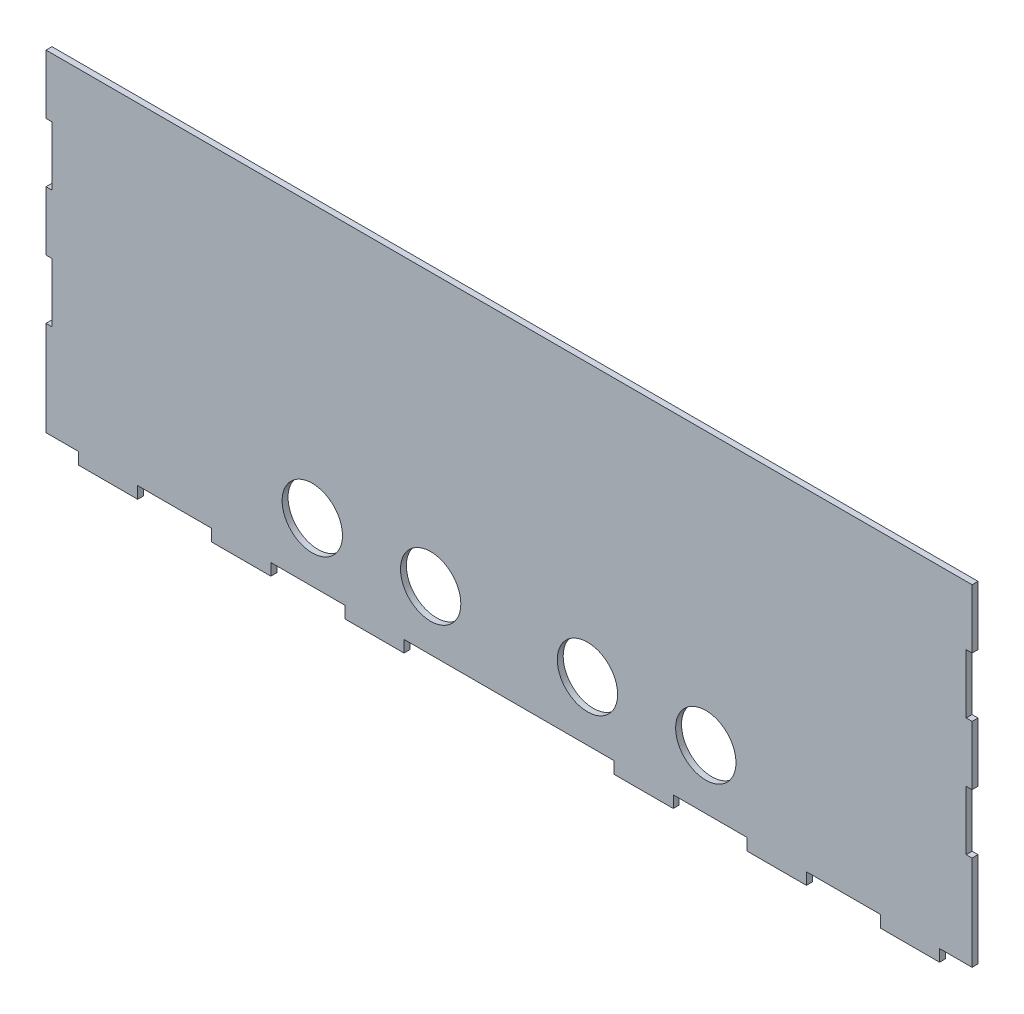
SolidWorks part; units mm, degrees
ref_plane "Front Plane" through (0, 0, 0) normal (0, 0, 1) x (1, 0, 0)
ref_plane "Top Plane" through (0, 0, 0) normal (0, 1, 0) x (1, 0, 0)
ref_plane "Right Plane" through (0, 0, 0) normal (1, 0, 0) x (0, 0, -1)
sketch "Sketch1" plane through (0, 0, 0) normal (0, 0, 1) x (1, 0, 0)
  line L0 (0, -55) -> (0, 55) construction
  line L1 (-156.5, -56) -> (-145.5, -56)
  line L2 (-156.5, -56) -> (-156.5, -24)
  line L3 (-156.5, 56) -> (-145.5, 56)
  line L4 (156.5, -56) -> (156.5, -24)
  line L5 (-156.5, -56) -> (156.5, 56) construction
  line L6 (-156.5, 56) -> (156.5, -56) construction
  line L7 (-100.5, -56) -> (-100.5, -60)
  line L9 (-145.5, -56) -> (-145.5, -60)
  line L10 (-145.5, -60) -> (-125.5, -60)
  line L11 (-125.5, -56) -> (-125.5, -60)
  line L13 (-80.5, -56) -> (-80.5, -60)
  line L14 (-100.5, -60) -> (-80.5, -60)
  line L15 (-55.5, -56) -> (-55.5, -60)
  line L17 (-35.5, -56) -> (-35.5, -60)
  line L18 (-55.5, -60) -> (-35.5, -60)
  line L20 (35.5, -56) -> (35.5, -60)
  line L21 (55.5, -60) -> (35.5, -60)
  line L22 (55.5, -56) -> (55.5, -60)
  line L24 (80.5, -56) -> (80.5, -60)
  line L25 (100.5, -60) -> (80.5, -60)
  line L26 (100.5, -56) -> (100.5, -60)
  line L27 (145.5, -60) -> (125.5, -60)
  line L28 (125.5, -56) -> (125.5, -60)
  line L30 (145.5, -56) -> (145.5, -60)
  line L31 (55.5, -56) -> (80.5, -56)
  line L32 (100.5, -56) -> (125.5, -56)
  line L33 (145.5, -56) -> (156.5, -56)
  line L34 (-125.5, -56) -> (-100.5, -56)
  line L35 (-80.5, -56) -> (-55.5, -56)
  line L36 (-35.5, -56) -> (35.5, -56)
  line L38 (-156.5, 36) -> (-154.5, 36)
  line L40 (-156.5, 16) -> (-154.5, 16)
  line L41 (-154.5, 36) -> (-154.5, 16)
  line L42 (-156.5, -4) -> (-154.5, -4)
  line L43 (-154.5, -4) -> (-154.5, -24)
  line L44 (-156.5, -24) -> (-154.5, -24)
  line L45 (156.5, -4) -> (154.5, -4)
  line L46 (154.5, -4) -> (154.5, -24)
  line L47 (156.5, -24) -> (154.5, -24)
  line L49 (156.5, 16) -> (154.5, 16)
  line L50 (154.5, 36) -> (154.5, 16)
  line L51 (156.5, 36) -> (154.5, 36)
  line L53 (-156.5, 36) -> (-156.5, 56)
  line L54 (-156.5, -4) -> (-156.5, 16)
  line L55 (156.5, 36) -> (156.5, 56)
  line L56 (156.5, -4) -> (156.5, 16)
  line L57 (-100.5, 56) -> (-100.5, 58)
  line L88 (-145.5, 56) -> (-145.5, 58)
  line L89 (-145.5, 58) -> (-125.5, 58)
  line L90 (-125.5, 56) -> (-125.5, 58)
  line L92 (-80.5, 56) -> (-80.5, 58)
  line L93 (-100.5, 58) -> (-80.5, 58)
  line L94 (-55.5, 56) -> (-55.5, 58)
  line L96 (-35.5, 56) -> (-35.5, 58)
  line L97 (-55.5, 58) -> (-35.5, 58)
  line L99 (35.5, 56) -> (35.5, 58)
  line L100 (55.5, 58) -> (35.5, 58)
  line L101 (55.5, 56) -> (55.5, 58)
  line L103 (80.5, 56) -> (80.5, 58)
  line L104 (100.5, 58) -> (80.5, 58)
  line L105 (100.5, 56) -> (100.5, 58)
  line L106 (145.5, 58) -> (125.5, 58)
  line L107 (125.5, 56) -> (125.5, 58)
  line L109 (145.5, 56) -> (145.5, 58)
  line L110 (-125.5, 56) -> (-100.5, 56)
  line L111 (-80.5, 56) -> (-55.5, 56)
  line L112 (-35.5, 56) -> (35.5, 56)
  line L113 (145.5, 56) -> (156.5, 56)
  line L114 (55.5, 56) -> (80.5, 56)
  line L115 (100.5, 56) -> (125.5, 56)
  circle A0 centre (-66.5, -36) radius 10.2
  circle A1 centre (-26.5, -36) radius 10.2
  circle A2 centre (26.5, -36) radius 10.2
  circle A3 centre (66.5, -36) radius 10.2
  point P0 (0, 0)
  dimension "D3" = 20.4
  dimension "D4" = 20.4
  dimension "D1" = 313
  dimension "D2" = 112
  dimension "D5" = 20
  dimension "D6" = 20
  dimension "D7" = 90
  dimension "D8" = 40
  dimension "D9" = 4
  dimension "D10" = 11
  dimension "D11" = 20
  dimension "D13" = 25
  dimension "D14" = 20
  dimension "D15" = 2
  dimension "D16" = 20
  dimension "D18" = 20
  dimension "D24" = 2
  dimension "D25" = 11
  dimension "D26" = 20
  dimension "D27" = 3
  dimension "D28" = 25
  dimension "D12" = 3
  dimension "D17" = 2
extrude "Boss-Extrude1" add sketch "Sketch1" along normal blind 2
sketch "Sketch2" plane through (0, 0, 2) normal (0, 0, 1) x (1, 0, 0)
  line L0 (145.5, -56) -> (156.5, -56) construction
  line L1 (134.5, -16) -> (114.5, -16)
  line L2 (134.5, -16) -> (134.5, -14)
  line L3 (134.5, -14) -> (114.5, -14)
  line L4 (114.5, -16) -> (114.5, -14)
  line L5 (134.5, -16) -> (114.5, -14) construction
  line L6 (134.5, -14) -> (114.5, -16) construction
  line L7 (154.5, -24) -> (154.5, -4) construction
  line L8 (104.5, -16) -> (104.5, -14)
  line L9 (104.5, -16) -> (84.5, -16)
  line L10 (84.5, -16) -> (84.5, -14)
  line L11 (104.5, -14) -> (84.5, -14)
  line L12 (74.5, -16) -> (74.5, -14)
  line L13 (74.5, -16) -> (54.5, -16)
  line L14 (54.5, -16) -> (54.5, -14)
  line L15 (74.5, -14) -> (54.5, -14)
  line L16 (-35.5, -56) -> (35.5, -56) construction
  line L17 (39.5, -16) -> (19.5, -16)
  line L18 (39.5, -16) -> (39.5, -14)
  line L19 (39.5, -14) -> (19.5, -14)
  line L20 (19.5, -16) -> (19.5, -14)
  line L21 (39.5, -16) -> (19.5, -14) construction
  line L22 (39.5, -14) -> (19.5, -16) construction
  line L23 (9.5, -16) -> (9.5, -14)
  line L24 (9.5, -16) -> (-10.5, -16)
  line L25 (-10.5, -16) -> (-10.5, -14)
  line L26 (9.5, -14) -> (-10.5, -14)
  line L27 (-20.5, -16) -> (-20.5, -14)
  line L28 (-20.5, -16) -> (-40.5, -16)
  line L29 (-40.5, -16) -> (-40.5, -14)
  line L30 (-20.5, -14) -> (-40.5, -14)
  line L31 (-50.5, -16) -> (-50.5, -14)
  line L32 (-50.5, -16) -> (-70.5, -16)
  line L33 (-70.5, -16) -> (-70.5, -14)
  line L34 (-50.5, -14) -> (-70.5, -14)
  point P0 (124.5, -15)
  point P10 (29.5, -15)
  dimension "D1" = 20
  dimension "D2" = 2
  dimension "D3" = 40
  dimension "D4" = 20
  dimension "D6" = 10
  dimension "D7" = 2
  dimension "D8" = 20
  dimension "D9" = 15
  dimension "D10" = 40
  dimension "D12" = 10
  dimension "D5" = 3
  dimension "D11" = 4
extrude "Cut-Extrude1" [suppressed] cut sketch "Sketch2" against normal blind 10
sketch "Sketch3" plane through (0, 0, 0) normal (0, 0, -1) x (-1, 0, 0)
  line L0 (-80.5, 56) -> (-55.5, 56) construction
  line L2 (-156.5, 36) -> (-156.5, 56) construction
  line L3 (-35.5, 56) -> (35.5, 56) construction
  line L4 (-46.5, 25.5) -> (-44.5, 25.5)
  line L5 (-46.5, 25.5) -> (-46.5, 40.5)
  line L6 (-46.5, 40.5) -> (-44.5, 40.5)
  line L7 (-44.5, 25.5) -> (-44.5, 40.5)
  line L8 (-46.5, 25.5) -> (-44.5, 40.5) construction
  line L9 (-46.5, 40.5) -> (-44.5, 25.5) construction
  line L10 (-68.5, 25.5) -> (-66.5, 25.5)
  line L11 (-68.5, 25.5) -> (-68.5, 40.5)
  line L12 (-68.5, 40.5) -> (-66.5, 40.5)
  line L13 (-66.5, 25.5) -> (-66.5, 40.5)
  line L14 (-68.5, 25.5) -> (-66.5, 40.5) construction
  line L15 (-68.5, 40.5) -> (-66.5, 25.5) construction
  line L16 (31.5, 25.5) -> (33.5, 25.5)
  line L17 (31.5, 25.5) -> (31.5, 40.5)
  line L18 (31.5, 40.5) -> (33.5, 40.5)
  line L19 (33.5, 25.5) -> (33.5, 40.5)
  line L20 (31.5, 25.5) -> (33.5, 40.5) construction
  line L21 (31.5, 40.5) -> (33.5, 25.5) construction
  line L22 (53.5, 25.5) -> (55.5, 25.5)
  line L23 (53.5, 25.5) -> (53.5, 40.5)
  line L24 (53.5, 40.5) -> (55.5, 40.5)
  line L25 (55.5, 25.5) -> (55.5, 40.5)
  line L26 (53.5, 25.5) -> (55.5, 40.5) construction
  line L27 (53.5, 40.5) -> (55.5, 25.5) construction
  line L29 (55.5, 56) -> (80.5, 56) construction
  circle A0 centre (-56.5, 33) radius 4.25
  circle A1 centre (43.5, 33) radius 4.25
  point P8 (-45.5, 33)
  point P13 (-67.5, 33)
  point P18 (32.5, 33)
  point P23 (54.5, 33)
  dimension "D1" = 8.5
  dimension "D3" = 8.5
  dimension "D4" = 100
  dimension "D2" = 23
  dimension "D5" = 100
  dimension "D6" = 11
  dimension "D7" = 2
  dimension "D8" = 15
  dimension "D9" = 15.5
  dimension "D10" = 2
  dimension "D11" = 15
  dimension "D12" = 11
  dimension "D13" = 15.5
  dimension "D14" = 2
  dimension "D15" = 2
  dimension "D16" = 15
  dimension "D17" = 15
  dimension "D18" = 11
  dimension "D19" = 11
  dimension "D20" = 15.5
  dimension "D21" = 15.5
extrude "Cut-Extrude2" [suppressed] cut sketch "Sketch3" against normal through all
sketch "Sketch4" plane through (0, 0, 2) normal (0, 0, 1) x (1, 0, 0)
  line L0 (-100.5, 56) -> (-125.5, 56) construction
  line L1 (-106.5, 21) -> (-108.5, 21)
  line L2 (-106.5, 21) -> (-106.5, 41)
  line L3 (-106.5, 41) -> (-108.5, 41)
  line L4 (-108.5, 21) -> (-108.5, 41)
  line L6 (-154.5, 36) -> (-154.5, 16) construction
  dimension "D1" = 20
  dimension "D2" = 2
  dimension "D3" = 15
  dimension "D4" = 46
extrude "Cut-Extrude3" [suppressed] cut sketch "Sketch4" against normal blind 10
sketch "Sketch5" plane through (0, 0, 2) normal (0, 0, 1) x (1, 0, 0)
  line L1 (-145.5, 58) -> (-125.5, 58)
  line L2 (-145.5, 58) -> (-145.5, 56)
  line L3 (-145.5, 56) -> (-125.5, 56)
  line L4 (-125.5, 58) -> (-125.5, 56)
  line L5 (-100.5, 58) -> (-80.5, 58)
  line L6 (-100.5, 58) -> (-100.5, 56)
  line L7 (-100.5, 56) -> (-80.5, 56)
  line L8 (-80.5, 58) -> (-80.5, 56)
  line L9 (-55.5, 58) -> (-35.5, 58)
  line L10 (-55.5, 58) -> (-55.5, 56)
  line L11 (-55.5, 56) -> (-35.5, 56)
  line L12 (-35.5, 58) -> (-35.5, 56)
  line L13 (35.5, 58) -> (55.5, 58)
  line L14 (35.5, 58) -> (35.5, 56)
  line L15 (35.5, 56) -> (55.5, 56)
  line L16 (55.5, 58) -> (55.5, 56)
  line L17 (80.5, 58) -> (100.5, 58)
  line L18 (80.5, 58) -> (80.5, 56)
  line L19 (80.5, 56) -> (100.5, 56)
  line L20 (100.5, 58) -> (100.5, 56)
  line L21 (125.5, 58) -> (145.5, 58)
  line L22 (125.5, 58) -> (125.5, 56)
  line L23 (125.5, 56) -> (145.5, 56)
  line L24 (145.5, 58) -> (145.5, 56)
extrude "Cut-Extrude4" cut sketch "Sketch5" against normal through all both and the other way through all
sketch "Sketch6" plane through (0, 0, 2) normal (0, 0, 1) x (1, 0, 0)
  line L0 (156.5, 56) -> (-156.5, 56) construction
  line L1 (39.5, 29) -> (64.5, 29) construction
  line L2 (52, 29) -> (52, 46.5) construction
  line L3 (154.5, 16) -> (154.5, 36) construction
  line L4 (0, -55) -> (0, 55) construction
  line L5 (-39.5, 29) -> (-64.5, 29) construction
  line L6 (-52, 29) -> (-52, 46.5) construction
  circle A0 centre (52, 46.5) radius 4
  circle A1 centre (39.5, 29) radius 4
  circle A2 centre (64.5, 29) radius 4
  circle A3 centre (-64.5, 29) radius 4
  circle A4 centre (-39.5, 29) radius 4
  circle A5 centre (-52, 46.5) radius 4
  dimension "D1" = 8
  dimension "D2" = 8
  dimension "D3" = 8
  dimension "D4" = 9.5
  dimension "D5" = 27
  dimension "D6" = 27
  dimension "D7" = 12.5
  dimension "D8" = 90
extrude "Cut-Extrude5" [suppressed] cut sketch "Sketch6" against normal through all both and the other way through all
